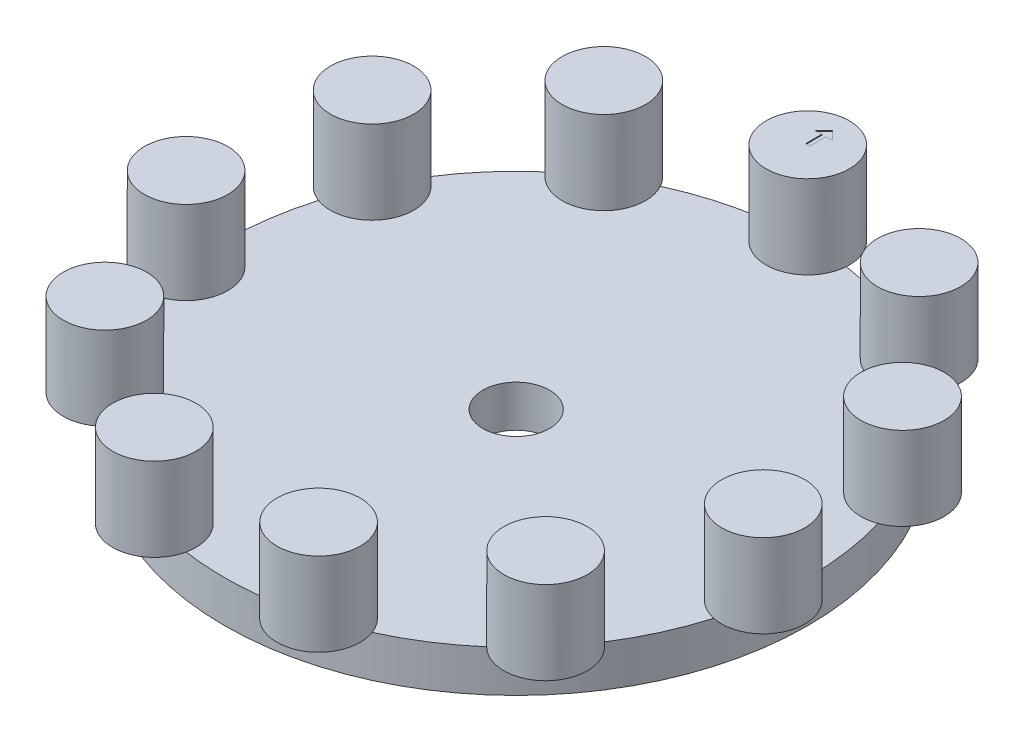
SolidWorks part; units mm, degrees
ref_plane "Front Plane" through (0, 0, 0) normal (0, 0, 1) x (1, 0, 0)
ref_plane "Top Plane" through (0, 0, 0) normal (0, 1, 0) x (1, 0, 0)
ref_plane "Right Plane" through (0, 0, 0) normal (1, 0, 0) x (0, 0, -1)
sketch "Sketch1" plane through (0, 0, 0) normal (0, 1, 0) x (1, 0, 0)
  circle A0 centre (0, 0) radius 35
  circle A1 centre (0, 35) radius 5
  circle A2 centre (18.9224, 29.4439) radius 5
  circle A3 centre (31.8371, 14.5395) radius 5
  circle A4 centre (34.6438, -4.981) radius 5
  circle A5 centre (26.4512, -22.9201) radius 5
  circle A6 centre (9.8606, -33.5823) radius 5
  circle A7 centre (-9.8606, -33.5823) radius 5
  circle A8 centre (-26.4512, -22.9201) radius 5
  circle A9 centre (-34.6438, -4.981) radius 5
  circle A10 centre (-31.8371, 14.5395) radius 5
  circle A11 centre (-18.9224, 29.4439) radius 5
  point P28 (0, 0)
  dimension "D1" = 70
  dimension "D2" = 11
  dimension "D3" = 10
extrude "Boss-Extrude1" add sketch "Sketch1" along normal blind 10 contours A0 A1 | A0 A1 | A0 A2 | A0 A2 | A0 A3 | A0 A3 | A0 A4 | A0 A4 | A0 A5 | A0 A5 | A0 A6 | A0 A6 | A0 A7 | A0 A7 | A0 A8 | A0 A8 | A0 A9 | A0 A9 | A0 A10 | A0 A10 | A0 A11 | A0 A11
sketch "Sketch2" plane through (0, 0, 0) normal (0, 1, 0) x (1, 0, 0)
  circle A0 centre (0, 0) radius 35
  circle A1 centre (0, 0) radius 4
extrude "Boss-Extrude2" add sketch "Sketch2" against normal blind 5
sketch "Sketch3" plane through (0, 10, 0) normal (0, 1, 0) x (1, 0, 0)
  line L0 (0, 35) -> (0, 38)
  line L1 (0, 38) -> (1.0607, 36.9393)
  line L2 (1.0607, 36.9393) -> (-1.0607, 36.9393)
  line L3 (-1.0607, 36.9393) -> (0, 38)
  line L4 (0.25, 35) -> (0.25, 38)
  line L5 (-0.25, 35) -> (-0.25, 38)
  line L6 (-0.25, 35) -> (0.25, 35)
  dimension "D1" = 0.25
  dimension "D2" = 0.25
extrude "Cut-Extrude1" cut sketch "Sketch3" against normal blind 0.1 contours L2 L5 L3 | L5 L2 L0 L3 | L2 L4 L1 L0 | L4 L2 L1 | L0 L6 L4 L2 | L5 L6 L0 L2
